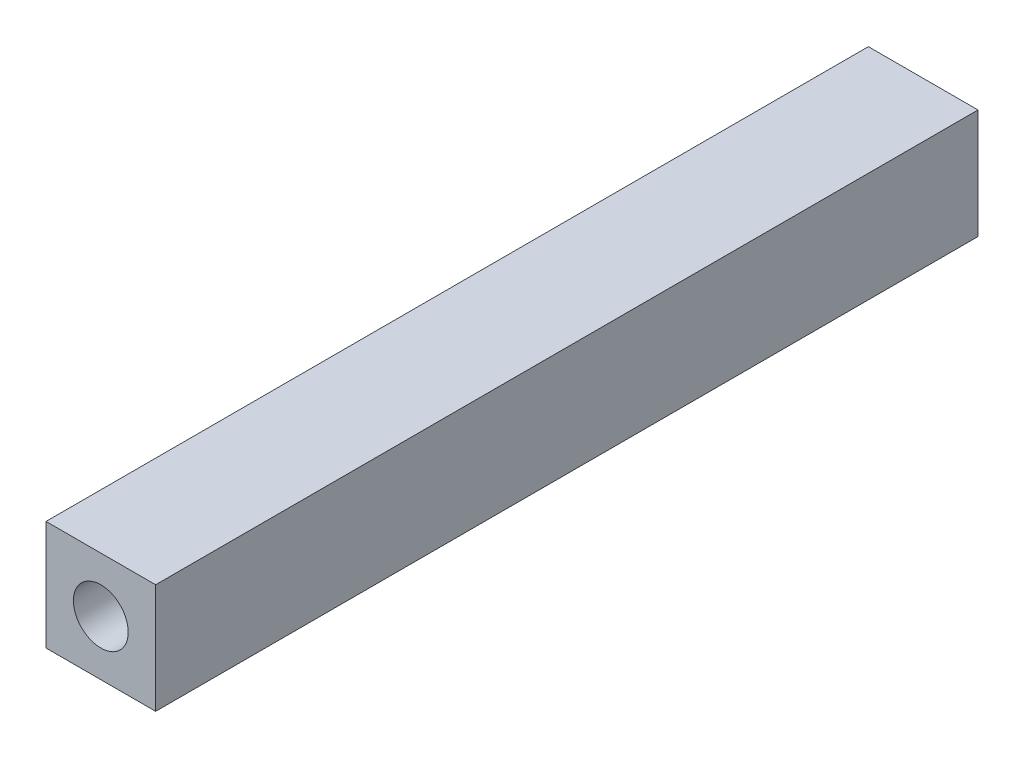
SolidWorks part; units mm, degrees
ref_plane "Front Plane" through (0, 0, 0) normal (0, 0, 1) x (1, 0, 0)
ref_plane "Top Plane" through (0, 0, 0) normal (0, 1, 0) x (1, 0, 0)
ref_plane "Right Plane" through (0, 0, 0) normal (1, 0, 0) x (0, 0, -1)
sketch "Sketch1" plane through (0, 0, 0) normal (0, 0, 1) x (1, 0, 0)
  line L1 (-10, -10) -> (10, -10)
  line L2 (-10, -10) -> (-10, 10)
  line L3 (-10, 10) -> (10, 10)
  line L4 (10, -10) -> (10, 10)
  line L5 (-10, -10) -> (10, 10) construction
  line L6 (-10, 10) -> (10, -10) construction
  circle A0 centre (0, 0) radius 5
  point P0 (0, 0)
  dimension "D1" = 10
  dimension "D2" = 20
  dimension "D3" = 20
extrude "Boss-Extrude1" add sketch "Sketch1" along normal blind 150
